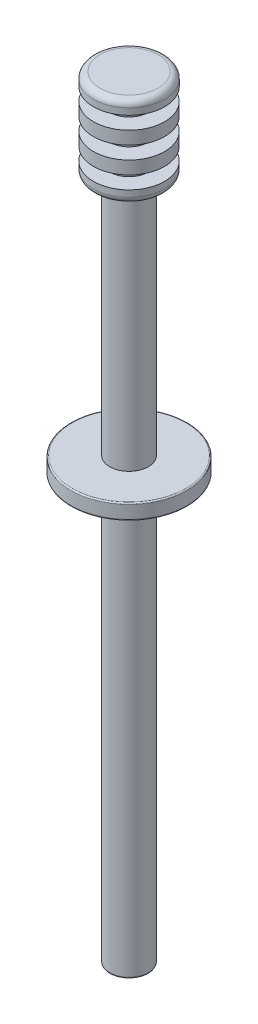
SolidWorks part; units mm, degrees
ref_plane "Front Plane" through (0, 0, 0) normal (0, 0, 1) x (1, 0, 0)
ref_plane "Top Plane" through (0, 0, 0) normal (0, 1, 0) x (1, 0, 0)
ref_plane "Right Plane" through (0, 0, 0) normal (1, 0, 0) x (0, 0, -1)
sketch "Sketch1" plane through (0, 0, 0) normal (0, 1, 0) x (1, 0, 0)
  circle A0 centre (0, 0) radius 2.75
  dimension "D1" = 5.5
extrude "Boss-Extrude1" add sketch "Sketch1" along normal blind 1
sketch "Sketch2" plane through (0, 0, 0) normal (0, -1, 0) x (1, 0, 0)
  circle A0 centre (0, 0) radius 1.5
  dimension "D1" = 3
extrude "Boss-Extrude2" add sketch "Sketch2" along normal blind 1
sketch "Sketch3" plane through (0, -1, 0) normal (0, -1, 0) x (-1, 0, 0)
  circle A0 centre (0, 0) radius 2.75
extrude "Boss-Extrude3" add sketch "Sketch3" along normal blind 1
sketch "Sketch4" plane through (0, -2, 0) normal (0, -1, 0) x (-1, 0, 0)
  circle A0 centre (0, 0) radius 1.5
  dimension "D1" = 3
extrude "Boss-Extrude4" add sketch "Sketch4" along normal blind 1
sketch "Sketch5" plane through (0, -3, 0) normal (0, -1, 0) x (-1, 0, 0)
  circle A0 centre (0, 0) radius 2.75
extrude "Boss-Extrude5" add sketch "Sketch5" along normal blind 1
sketch "Sketch6" plane through (0, -4, 0) normal (0, -1, 0) x (1, 0, 0)
  circle A0 centre (0, 0) radius 1.5
  dimension "D1" = 3
extrude "Boss-Extrude6" add sketch "Sketch6" along normal blind 1
sketch "Sketch7" plane through (0, -5, 0) normal (0, -1, 0) x (1, 0, 0)
  circle A0 centre (0, 0) radius 2.75
extrude "Boss-Extrude7" add sketch "Sketch7" along normal blind 1
sketch "Sketch8" plane through (0, -6, 0) normal (0, -1, 0) x (-1, 0, 0)
  circle A0 centre (0, 0) radius 1.5
  dimension "D1" = 3
extrude "Boss-Extrude8" add sketch "Sketch8" along normal blind 18.75
sketch "Sketch9" plane through (0, -24.75, 0) normal (0, -1, 0) x (-1, 0, 0)
  circle A0 centre (0, 0) radius 4.5
  dimension "D1" = 9
extrude "Boss-Extrude9" add sketch "Sketch9" along normal blind 1.2
sketch "Sketch10" plane through (0, -25.95, 0) normal (0, -1, 0) x (1, 0, 0)
  circle A0 centre (0, 0) radius 1.5
  dimension "D1" = 3
extrude "Boss-Extrude10" add sketch "Sketch10" along normal blind 32.81
fillet "Fillet1" radius 0.5 1 edges at (0, 1, 2.75)
fillet "Fillet2" radius 0.1 2 edges at (0, -24.75, -4.5) (0, -25.95, -4.5)
fillet "Fillet3" radius 0.5 1 edges at (0, -6, -2.75)
fillet "Fillet4" radius 0.1 1 edges at (0, -58.76, -1.5)
